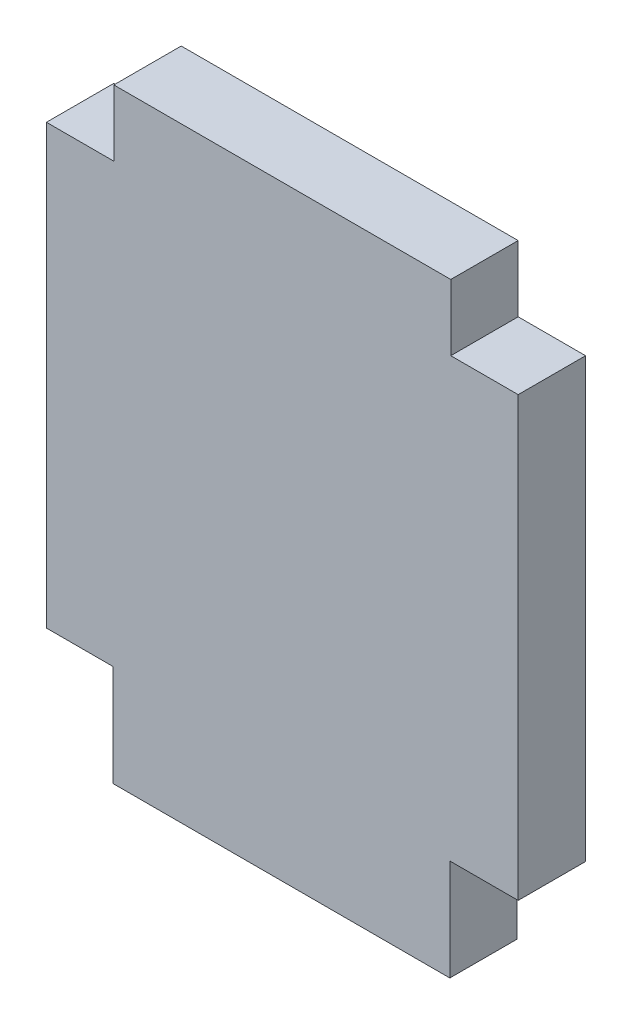
SolidWorks part; units mm, degrees
ref_plane "Front Plane" through (0, 0, 0) normal (0, 0, 1) x (1, 0, 0)
ref_plane "Top Plane" through (0, 0, 0) normal (0, 1, 0) x (1, 0, 0)
ref_plane "Right Plane" through (0, 0, 0) normal (1, 0, 0) x (0, 0, -1)
sketch "Sketch1" plane through (0, 0, 0) normal (0, 0, 1) x (1, 0, 0)
  line L0 (48.7196, 135.9652) -> (43.6396, 135.9652)
  line L1 (3.1927, 122.5275) -> (64.0307, 122.5275) construction
  line L2 (48.7196, 135.9652) -> (48.7196, 122.5275)
  line L4 (48.7196, 102.9452) -> (43.5672, 102.9452)
  line L5 (43.5672, 102.9452) -> (43.5672, 95.3054)
  line L6 (43.5672, 95.3054) -> (18.1672, 95.3054)
  line L7 (18.1672, 95.3054) -> (18.1672, 102.9452)
  line L8 (18.1672, 102.9452) -> (13.1596, 102.9452)
  line L9 (13.1596, 102.9452) -> (13.1596, 122.5275)
  line L10 (13.1596, 135.9652) -> (18.2396, 135.9652)
  line L11 (18.2396, 135.9652) -> (18.2396, 140.9433)
  line L12 (18.2396, 140.9433) -> (43.6396, 140.9433)
  line L13 (43.6396, 140.9433) -> (43.6396, 135.9652)
  line L14 (63.9582, 122.5275) -> (8.2511, 122.5275) construction
  line L15 (13.1596, 122.5275) -> (13.1596, 135.9652)
  line L16 (48.7196, 122.5275) -> (48.7196, 102.9452)
extrude "Boss-Extrude1" add sketch "Sketch1" along normal blind 5.08 contours L12 L13 L0 L2 L16 L4 L5 L6 L7 L8 L9 L15 L10 L11
